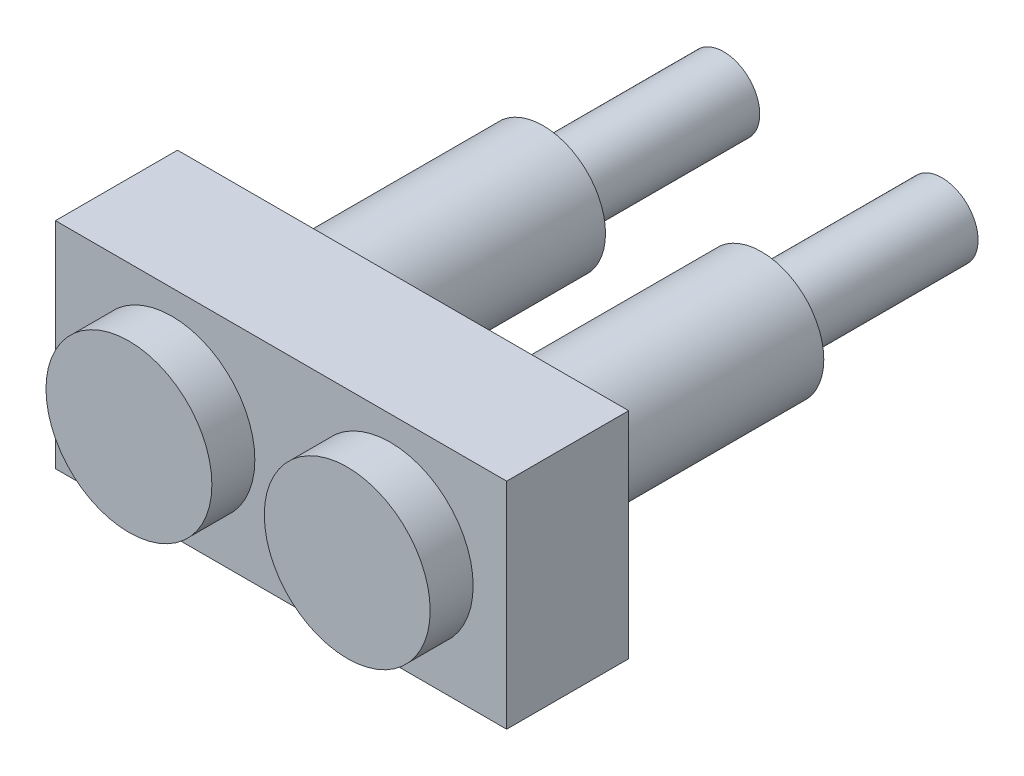
SolidWorks part; units mm, degrees
ref_plane "正面" through (0, 0, 0) normal (0, 0, 1) x (1, 0, 0)
ref_plane "平面" through (0, 0, 0) normal (0, 1, 0) x (1, 0, 0)
ref_plane "右側面" through (0, 0, 0) normal (1, 0, 0) x (0, 0, -1)
sketch "ｽｹｯﾁ1" plane through (0, 0, 0) normal (0, 0, 1) x (1, 0, 0)
  line L1 (2.625, -1.25) -> (-2.625, -1.25)
  line L2 (2.625, -1.25) -> (2.625, 1.25)
  line L3 (2.625, 1.25) -> (-2.625, 1.25)
  line L4 (-2.625, -1.25) -> (-2.625, 1.25)
  line L5 (2.625, -1.25) -> (-2.625, 1.25) construction
  line L6 (2.625, 1.25) -> (-2.625, -1.25) construction
  point P0 (0, 0)
  dimension "D1" = 5.25
  dimension "D2" = 2.5
extrude "ﾎﾞｽ - 押し出し1" add sketch "ｽｹｯﾁ1" along normal blind 1.42
sketch "ｽｹｯﾁ2" plane through (0, 0, 0) normal (0, 0, -1) x (-1, 0, 0)
  line L0 (0, 1.25) -> (0, -1.25) construction
  line L1 (-2.625, 1.25) -> (2.625, 1.25) construction
  line L2 (2.625, -1.25) -> (-2.625, -1.25) construction
  line L3 (-2.625, 0) -> (2.625, 0) construction
  line L4 (-2.625, -1.25) -> (-2.625, 1.25) construction
  line L5 (2.625, 1.25) -> (2.625, -1.25) construction
  circle A0 centre (-1.27, 0) radius 0.725
  circle A1 centre (1.27, 0) radius 0.725
  dimension "D1" = 1.45
  dimension "D2" = 1.27
extrude "ﾎﾞｽ - 押し出し2" add sketch "ｽｹｯﾁ2" along normal blind 5
sketch "ｽｹｯﾁ3" plane through (0, 0, 1.42) normal (0, 0, 1) x (1, 0, 0)
  circle A0 centre (-1.27, 0) radius 0.965
  circle A1 centre (1.27, 0) radius 0.965
  dimension "D1" = 1.93
extrude "ﾎﾞｽ - 押し出し3" add sketch "ｽｹｯﾁ3" along normal blind 0.5
sketch "ｽｹｯﾁ4" plane through (0, 0, -5) normal (0, 0, -1) x (-1, 0, 0)
  circle A0 centre (-1.27, 0) radius 0.725
  circle A1 centre (-1.27, 0) radius 0.42
  circle A2 centre (1.27, 0) radius 0.725
  circle A3 centre (1.27, 0) radius 0.42
  circle A4 centre (-1.27, 0) radius 0.725 construction
  dimension "D1" = 0.84
extrude "ｶｯﾄ - 押し出し1" cut sketch "ｽｹｯﾁ4" against normal blind 2.1
